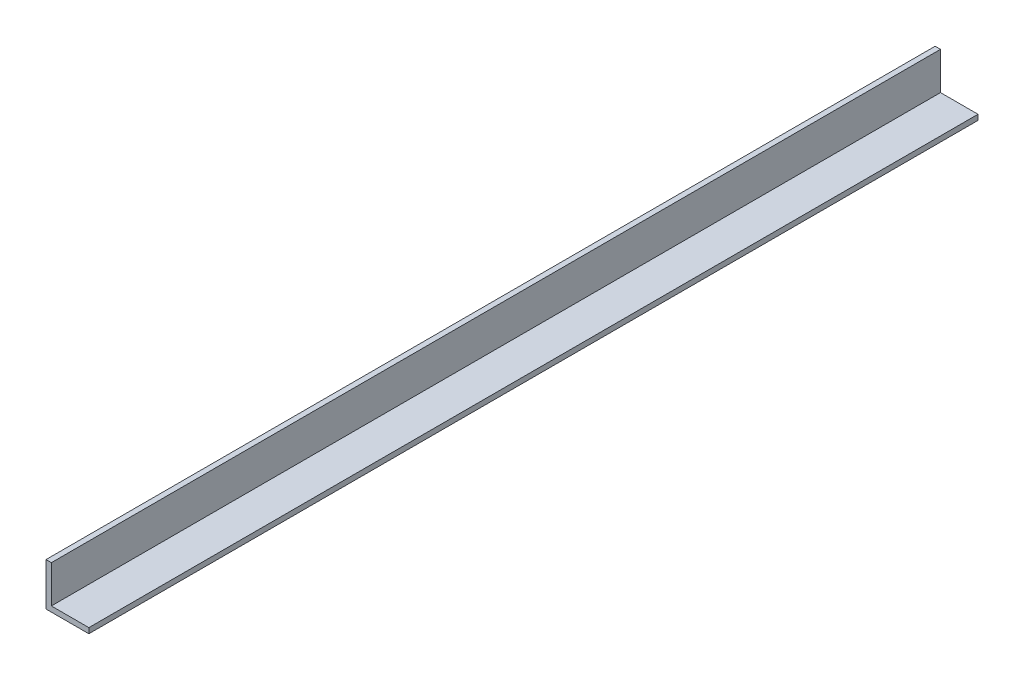
SolidWorks part; units mm, degrees
material "6061 Alloy"
ref_plane "Front Plane" through (0, 0, 0) normal (0, 0, 1) x (1, 0, 0)
ref_plane "Top Plane" through (0, 0, 0) normal (0, 1, 0) x (1, 0, 0)
ref_plane "Right Plane" through (0, 0, 0) normal (1, 0, 0) x (0, 0, -1)
sketch "Sketch1" plane through (0, 0, 0) normal (0, 0, 1) x (1, 0, 0)
  line L1 (0, 0) -> (25.4, 0)
  line L2 (0, 0) -> (0, -25.4)
  line L3 (0, -25.4) -> (25.4, -25.4)
  line L4 (25.4, 0) -> (25.4, -25.4)
extrude "Boss-Extrude1" add sketch "Sketch1" along normal blind 527.05
sketch "Sketch2" plane through (0, 0, 527.05) normal (0, 0, 1) x (1, 0, 0)
  line L0 (25.4, 0) -> (0, 0) construction
  line L1 (3.175, 0) -> (25.4, 0)
  line L2 (3.175, 0) -> (3.175, -22.225)
  line L3 (3.175, -22.225) -> (25.4, -22.225)
  line L4 (25.4, 0) -> (25.4, -22.225)
  line L5 (25.4, -25.4) -> (25.4, 0) construction
  line L6 (0, 0) -> (0, -25.4) construction
  line L7 (0, -25.4) -> (25.4, -25.4) construction
  dimension "D1" = 3.175
  dimension "D2" = 3.175
extrude "Cut-Extrude1" cut sketch "Sketch2" against normal through all
